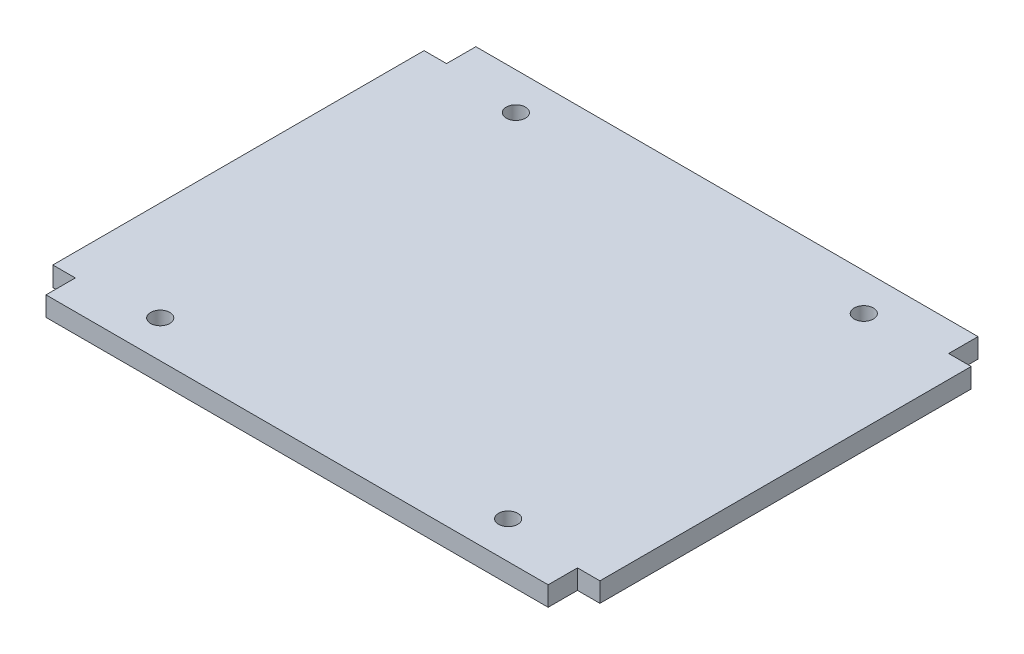
SolidWorks part; units mm, degrees
ref_plane "Front Plane" through (0, 0, 0) normal (0, 0, 1) x (1, 0, 0)
ref_plane "Top Plane" through (0, 0, 0) normal (0, 1, 0) x (1, 0, 0)
ref_plane "Right Plane" through (0, 0, 0) normal (1, 0, 0) x (0, 0, -1)
sketch "Sketch2" plane through (0, 0, 0) normal (0, 1, 0) x (1, 0, 0)
  line L0 (-22.615, 23.115) -> (22.615, 23.115) construction
  line L1 (-55, 0) -> (55, 0) construction
  line L2 (32.639, 24.13) -> (35.56, 24.13)
  line L3 (-32.639, -27.94) -> (32.639, -27.94)
  line L4 (-32.639, -27.94) -> (-32.639, -24.13)
  line L5 (-32.639, 27.94) -> (32.639, 27.94)
  line L6 (32.639, -27.94) -> (32.639, -24.13)
  line L7 (-32.639, -27.94) -> (32.639, 27.94) construction
  line L8 (-32.639, 27.94) -> (32.639, -27.94) construction
  line L9 (32.639, -24.13) -> (35.56, -24.13)
  line L10 (35.56, 24.13) -> (35.56, -24.13)
  line L11 (0, -55) -> (0, 55) construction
  line L12 (-32.639, -24.13) -> (-35.56, -24.13)
  line L13 (-35.56, 24.13) -> (-35.56, -24.13)
  line L14 (-32.639, 24.13) -> (-35.56, 24.13)
  line L15 (-32.639, 24.13) -> (-32.639, 27.94)
  line L16 (32.639, 24.13) -> (32.639, 27.94)
  circle A0 centre (-22.615, 23.115) radius 1.25
  circle A1 centre (22.615, 23.115) radius 1.25
  circle A2 centre (22.615, -23.115) radius 1.25
  circle A3 centre (-22.615, -23.115) radius 1.25
  point P4 (0, 23.115)
  point P12 (0, 0)
  dimension "D1" = 45.23
  dimension "D3" = 2.5
  dimension "D5" = 65.278
  dimension "D2" = 46.23
  dimension "D4" = 55.88
  dimension "D6" = 48.26
  dimension "D7" = 35.56
extrude "Boss-Extrude2" add sketch "Sketch2" along normal mid plane 2.54
